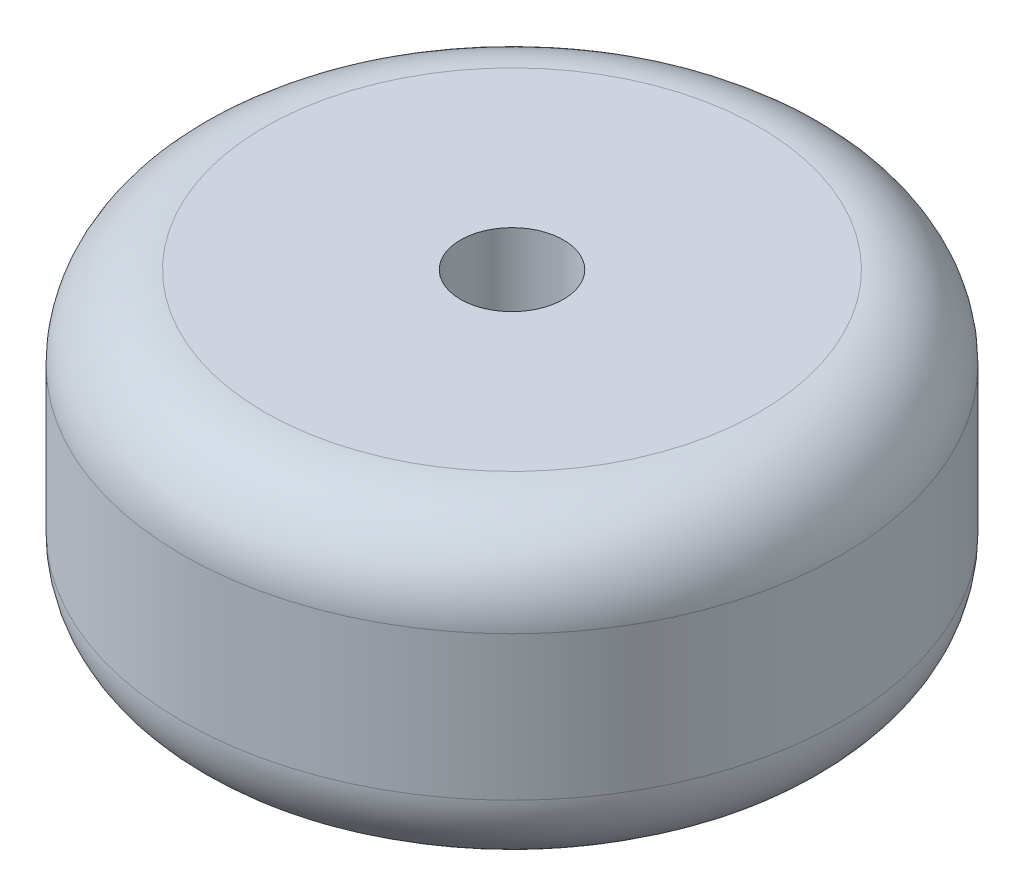
SolidWorks part; units mm, degrees
ref_plane "前视基准面" through (0, 0, 0) normal (0, 0, 1) x (1, 0, 0)
ref_plane "上视基准面" through (0, 0, 0) normal (0, 1, 0) x (1, 0, 0)
ref_plane "右视基准面" through (0, 0, 0) normal (1, 0, 0) x (0, 0, -1)
sketch "草图1" plane through (0, 0, 0) normal (0, 1, 0) x (1, 0, 0)
  circle A0 centre (0, 0) radius 16
  circle A1 centre (0, 0) radius 2.5
  dimension "D1" = 32
  dimension "D2" = 5
extrude "凸台-拉伸1" add sketch "草图1" along normal blind 15
fillet "圆角1" radius 4 2 edges at (0, 0, 16) (0, 15, 16)
